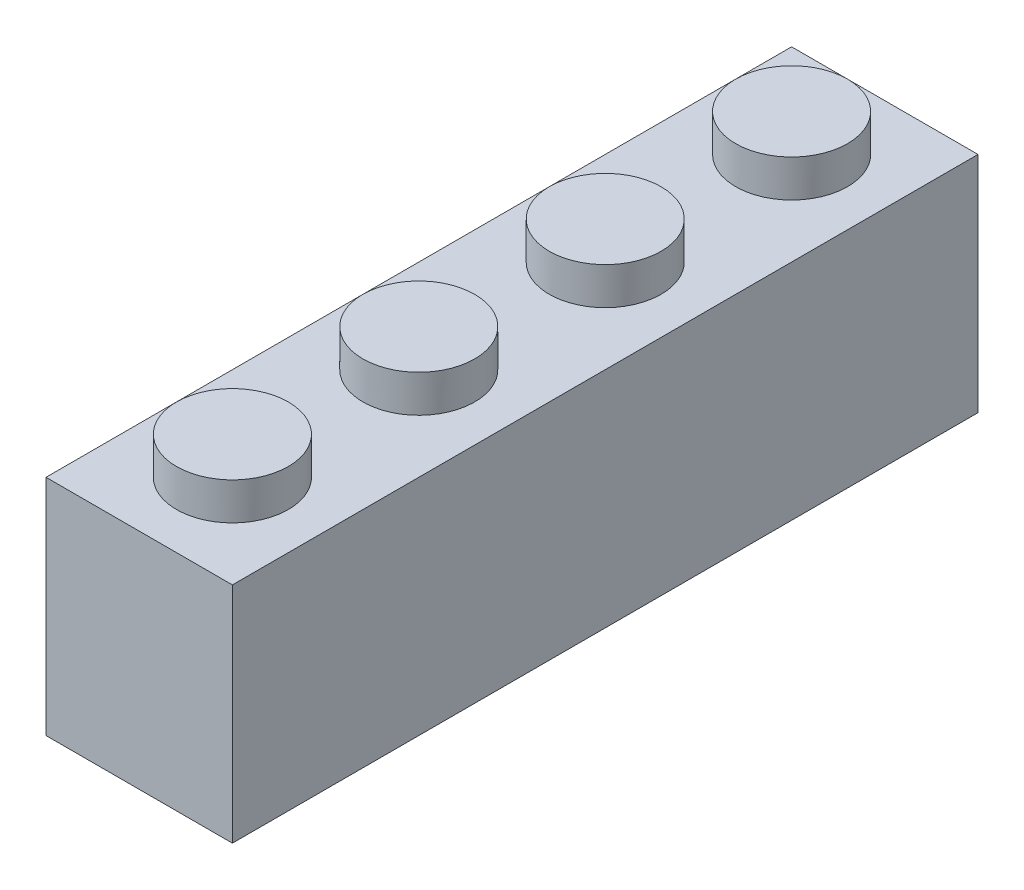
SolidWorks part; units mm, degrees
ref_plane "Front Plane" through (0, 0, 0) normal (0, 0, 1) x (1, 0, 0)
ref_plane "Top Plane" through (0, 0, 0) normal (0, 1, 0) x (1, 0, 0)
ref_plane "Right Plane" through (0, 0, 0) normal (1, 0, 0) x (0, 0, -1)
sketch "Sketch1" plane through (0, 0, 0) normal (0, 1, 0) x (1, 0, 0)
  line L1 (0, 0) -> (8, 0)
  line L2 (0, 0) -> (0, 32)
  line L3 (0, 32) -> (8, 32)
  line L4 (8, 0) -> (8, 32)
  dimension "D1" = 8
  dimension "D2" = 32
extrude "Boss-Extrude1" add sketch "Sketch1" along normal blind 9.6
sketch "Sketch2" plane through (0, 9.6, 0) normal (0, 1, 0) x (1, 0, 0)
  line L0 (4, 0) -> (4, 32) construction
  line L1 (0, 0) -> (8, 0) construction
  line L2 (8, 32) -> (0, 32) construction
  line L3 (8, 0) -> (8, 4) construction
  line L4 (8, 0) -> (8, 32) construction
  line L5 (8, 4) -> (4, 4) construction
  circle A0 centre (4, 4) radius 2.4
  dimension "D3" = 4.8
  dimension "D1" = 4
  dimension "D2" = 4
extrude "Boss-Extrude2" add sketch "Sketch2" along normal blind 1.6
pattern_linear "LPattern1" count 2 spacing 8 along (1, 0, 0) count 4 spacing 8 along (0, 0, -1) of "Boss-Extrude2"
shell "Shell1" thickness 1.6
